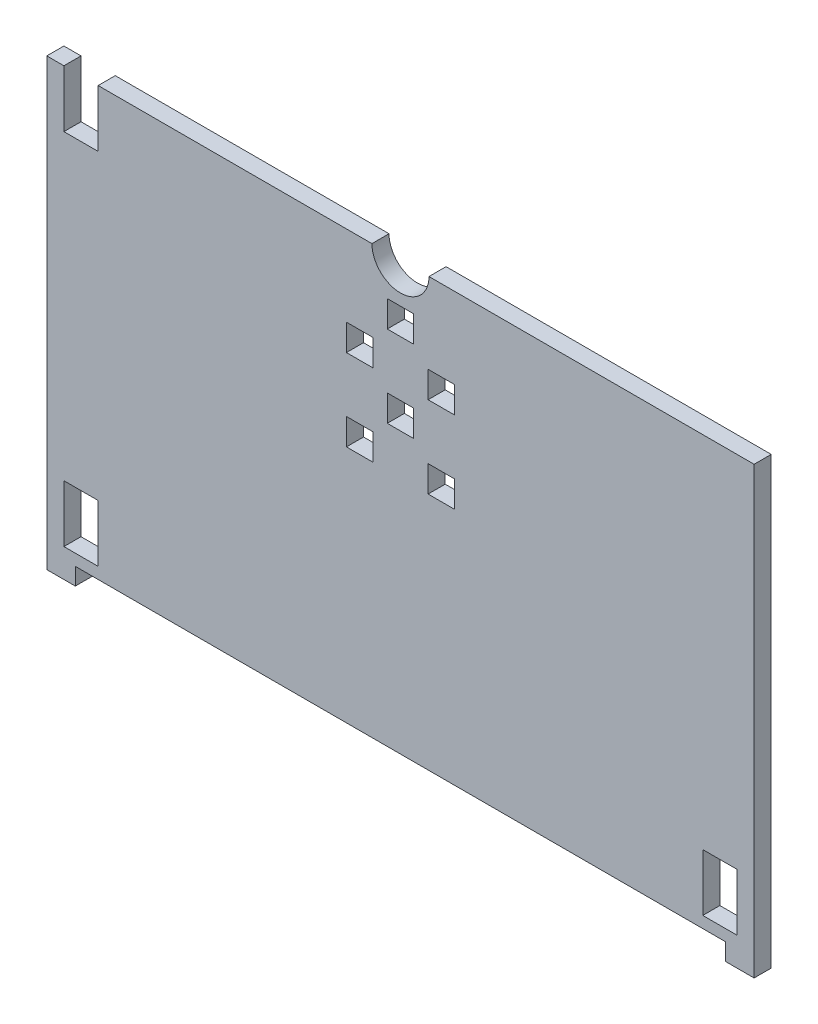
SolidWorks part; units mm, degrees
ref_plane "Front Plane" through (0, 0, 0) normal (0, 0, 1) x (1, 0, 0)
ref_plane "Top Plane" through (0, 0, 0) normal (0, 1, 0) x (1, 0, 0)
ref_plane "Right Plane" through (0, 0, 0) normal (1, 0, 0) x (0, 0, -1)
sketch "Sketch1" plane through (0, 0, 0) normal (0, 0, 1) x (1, 0, 0)
  line L0 (0, 0) -> (5, 0)
  line L1 (5, 0) -> (5, 3)
  line L2 (5, 3) -> (119, 3)
  line L3 (119, 3) -> (119, 0)
  line L4 (119, 0) -> (124, 0)
  line L5 (124, 0) -> (124, 78)
  line L6 (124, 78) -> (67, 78)
  line L7 (0, 78) -> (0, 0)
  line L8 (3, 78) -> (0, 78)
  line L9 (57, 78) -> (9, 78)
  line L10 (3, 78) -> (3, 68)
  line L11 (3, 68) -> (9, 68)
  line L12 (9, 78) -> (9, 68)
  line L13 (3, 15) -> (9, 15)
  line L14 (3, 15) -> (3, 5)
  line L15 (3, 5) -> (9, 5)
  line L16 (9, 15) -> (9, 5)
  line L17 (115, 15) -> (121, 15)
  line L18 (115, 15) -> (115, 5)
  line L19 (115, 5) -> (121, 5)
  line L20 (121, 15) -> (121, 5)
  arc A0 (57, 78) -> (67, 78) centre (62, 78) ccw
  dimension "D12" = 62
  dimension "D15" = 5
  dimension "D1" = 78
  dimension "D2" = 124
  dimension "D3" = 5
  dimension "D4" = 5
  dimension "D5" = 3
  dimension "D6" = 6
  dimension "D7" = 10
  dimension "D8" = 3
  dimension "D9" = 2
  dimension "D10" = 3
  dimension "D11" = 6
  dimension "D13" = 3
  dimension "D14" = 68
extrude "Boss-Extrude1" add sketch "Sketch1" along normal blind 3
sketch "Sketch2" plane through (0, 0, 3) normal (0, 0, 1) x (1, 0, 0)
  line L0 (124, 78) -> (67, 78) construction
  line L1 (52.53, 63.84) -> (57.15, 63.84)
  line L2 (52.53, 63.84) -> (52.53, 59.22)
  line L3 (52.53, 59.22) -> (57.15, 59.22)
  line L4 (57.15, 63.84) -> (57.15, 59.22)
  line L5 (66.85, 63.84) -> (71.47, 63.84)
  line L6 (66.85, 63.84) -> (66.85, 59.22)
  line L7 (66.85, 59.22) -> (71.47, 59.22)
  line L8 (71.47, 63.84) -> (71.47, 59.22)
  line L9 (52.53, 49.52) -> (57.15, 49.52)
  line L10 (52.53, 49.52) -> (52.53, 44.9)
  line L11 (52.53, 44.9) -> (57.15, 44.9)
  line L12 (57.15, 49.52) -> (57.15, 44.9)
  line L13 (66.85, 49.52) -> (71.47, 49.52)
  line L14 (66.85, 49.52) -> (66.85, 44.9)
  line L15 (66.85, 44.9) -> (71.47, 44.9)
  line L16 (71.47, 49.52) -> (71.47, 44.9)
  line L17 (59.69, 56.68) -> (64.31, 56.68)
  line L18 (59.69, 56.68) -> (59.69, 52.06)
  line L19 (59.69, 52.06) -> (64.31, 52.06)
  line L20 (64.31, 56.68) -> (64.31, 52.06)
  line L21 (59.69, 71) -> (64.31, 71)
  line L22 (59.69, 71) -> (59.69, 66.38)
  line L23 (59.69, 66.38) -> (64.31, 66.38)
  line L24 (64.31, 71) -> (64.31, 66.38)
  line L25 (124, 0) -> (124, 78) construction
  dimension "D1" = 4.62
  dimension "D2" = 9.7
  dimension "D3" = 9.7
  dimension "D4" = 7
  dimension "D5" = 59.69
  dimension "D6" = 2.54
  dimension "D7" = 9.7
  dimension "D8" = 2.54
extrude "Cut-Extrude1" cut sketch "Sketch2" against normal through all
